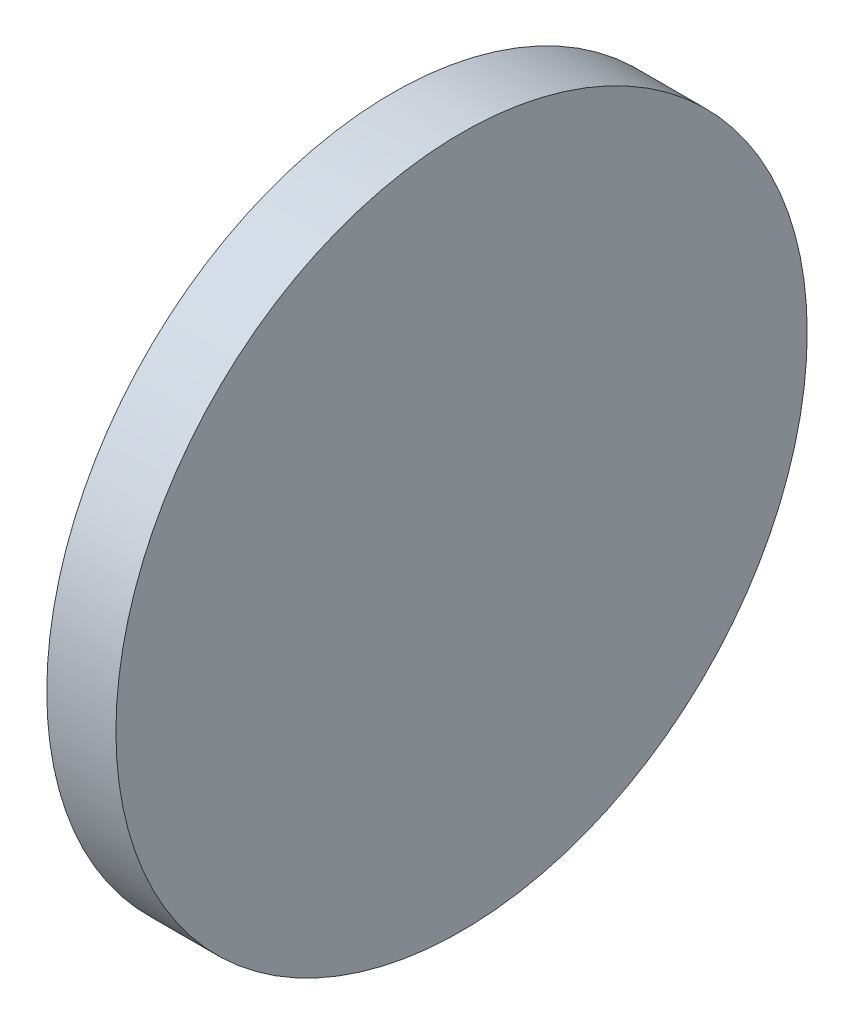
SolidWorks part; units mm, degrees
ref_plane "前视基准面" through (0, 0, 0) normal (0, 0, 1) x (1, 0, 0)
ref_plane "上视基准面" through (0, 0, 0) normal (0, 1, 0) x (1, 0, 0)
ref_plane "右视基准面" through (0, 0, 0) normal (1, 0, 0) x (0, 0, -1)
sketch "草图7" plane through (0, 0, 0) normal (0, 1, 0) x (0, 0, -1)
  line L0 (0, -1000) -> (0, 49000) construction
  line L1 (0, 0) -> (150, 0)
  line L2 (150, 0) -> (150, 30)
  line L3 (150, 30) -> (128.5, 30)
  line L4 (0, 0) -> (0, 12)
  arc A0 (0, 12) -> (128.5, 30) centre (0, 479.6736) ccw
  dimension "D1" = 150
  dimension "D2" = 128.5
  dimension "D3" = 30
  dimension "D4" = 12
revolve "旋转1" add sketch "草图7" angle 360 about L0
